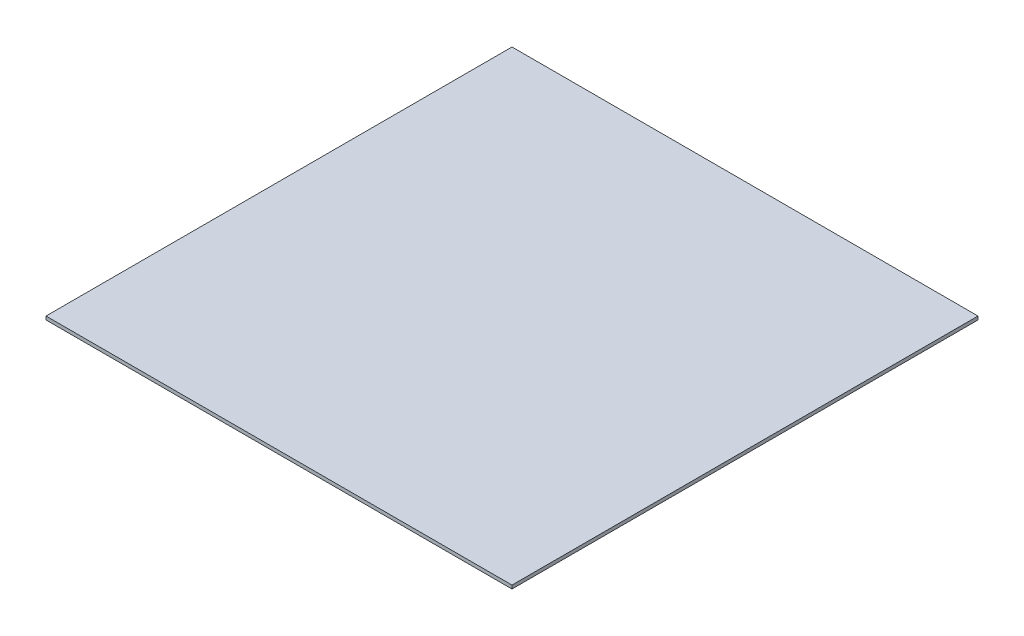
SolidWorks part; units mm, degrees
material "Plain Carbon Steel"
ref_plane "Front Plane" through (0, 0, 0) normal (0, 0, 1) x (1, 0, 0)
ref_plane "Top Plane" through (0, 0, 0) normal (0, 1, 0) x (1, 0, 0)
ref_plane "Right Plane" through (0, 0, 0) normal (1, 0, 0) x (0, 0, -1)
sketch "Sketch1" plane through (0, 0, 0) normal (0, 1, 0) x (1, 0, 0)
  circle A0 centre (0, 0) radius 2.1
  dimension "D1" = 4.2
extrude "Boss-Extrude1" add sketch "Sketch1" against normal blind 25
sketch "Sketch2" plane through (0, 0, 0) normal (0, 1, 0) x (1, 0, 0)
  line L1 (101.6, 101.6) -> (-101.6, 101.6)
  line L2 (101.6, 101.6) -> (101.6, -101.6)
  line L3 (101.6, -101.6) -> (-101.6, -101.6)
  line L4 (-101.6, 101.6) -> (-101.6, -101.6)
  line L5 (0, -101.6) -> (0, 101.6) construction
  line L6 (101.6, 0) -> (-101.6, 0) construction
  point P0 (0, 0)
  dimension "D1" = 203.2
  dimension "D2" = 203.2
extrude "Boss-Extrude2" add sketch "Sketch2" along normal blind 1.5
sketch "Sketch3" plane through (0, 0, 0) normal (0, 1, 0) x (1, 0, 0)
  circle A0 centre (0, 0) radius 10
  dimension "D1" = 20
extrude "Boss-Extrude3" add sketch "Sketch3" against normal blind 1
